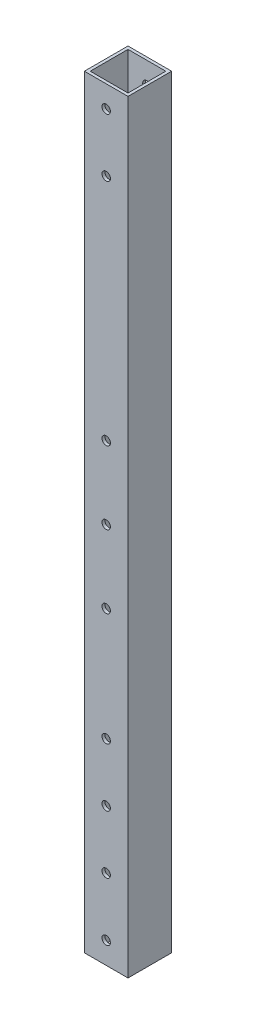
SolidWorks part; units mm, degrees
material "Thornel Mat VMA"
ref_plane "前视基准面" through (0, 0, 0) normal (0, 0, 1) x (1, 0, 0)
ref_plane "上视基准面" through (0, 0, 0) normal (0, 1, 0) x (1, 0, 0)
ref_plane "右视基准面" through (0, 0, 0) normal (1, 0, 0) x (0, 0, -1)
sketch "草图1" plane through (0, 0, 0) normal (0, 1, 0) x (1, 0, 0)
  line L1 (-7.5, -7.5) -> (7.5, -7.5)
  line L2 (-7.5, -7.5) -> (-7.5, 7.5)
  line L3 (-7.5, 7.5) -> (7.5, 7.5)
  line L4 (7.5, -7.5) -> (7.5, 7.5)
  line L5 (-7.5, -7.5) -> (7.5, 7.5) construction
  line L6 (-7.5, 7.5) -> (7.5, -7.5) construction
  point P0 (0, 0)
  dimension "D1" = 15
  dimension "D2" = 15
extrude "拉伸-薄壁1" add sketch "草图1" along normal blind 262.5 thin thin type one direction reverse wall 1
sketch "草图2" plane through (0, 0, 7.5) normal (0, 0, 1) x (1, 0, 0)
  line L0 (0, 0) -> (0, 262.5) construction
  line L1 (-7.5, 262.5) -> (7.5, 262.5) construction
  line L2 (0, 131.25) -> (-194.6638, 131.25) construction
  line L3 (-7.5, 0) -> (7.5, 0) construction
  circle A0 centre (0, 7.5) radius 1.45
  circle A1 centre (0, 27.5) radius 1.45
  circle A2 centre (0, 235) radius 1.45
  circle A3 centre (0, 255) radius 1.45
  circle A4 centre (0, 131.25) radius 1.45
  circle A5 centre (0, 106.25) radius 1.45
  circle A6 centre (0, 156.25) radius 1.45
  circle A7 centre (0, 47.5) radius 1.45
  circle A8 centre (0, 67.5) radius 1.45
  point P17 (0, 131.25)
  dimension "D1" = 2.9
  dimension "D3" = 20
  dimension "D4" = 2.9
  dimension "D5" = 25
  dimension "D6" = 25
  dimension "D7" = 20
  dimension "D2" = 7.5
  dimension "D8" = 20
extrude "切除-拉伸1" cut sketch "草图2" against normal through all
